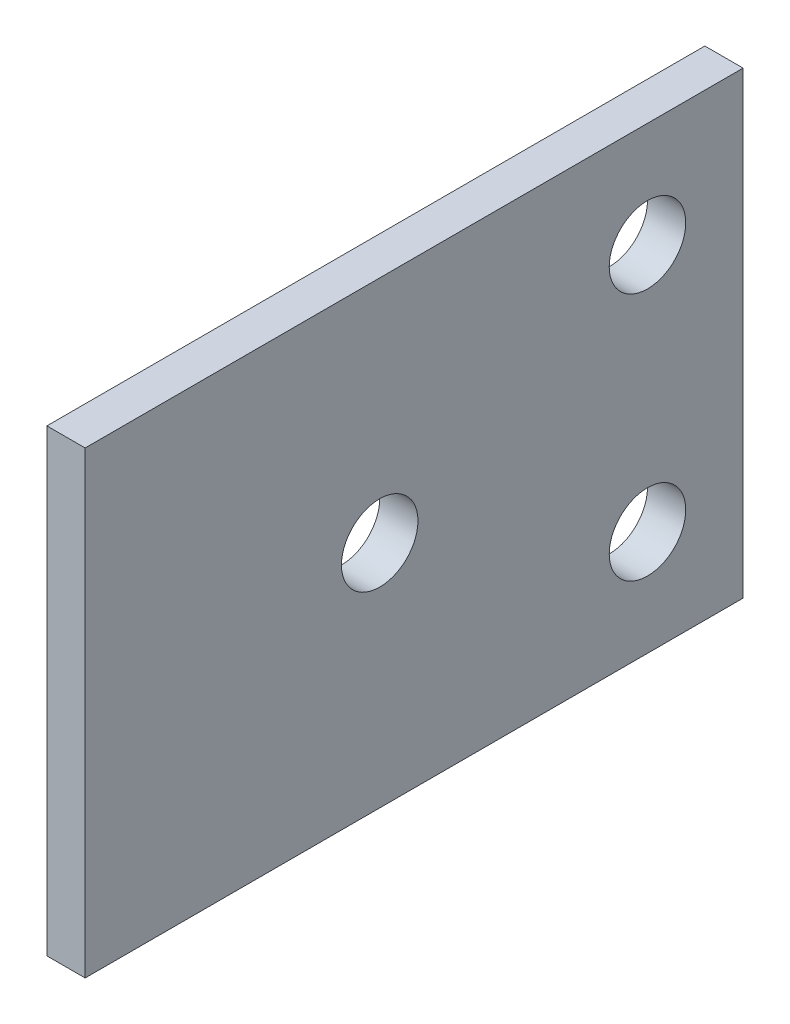
SolidWorks part; units mm, degrees
material "1023 Carbon Steel Sheet (SS)"
ref_plane "Front Plane" through (0, 0, 0) normal (0, 0, 1) x (1, 0, 0)
ref_plane "Top Plane" through (0, 0, 0) normal (0, 1, 0) x (1, 0, 0)
ref_plane "Right Plane" through (0, 0, 0) normal (1, 0, 0) x (0, 0, -1)
sketch "Sketch1" plane through (0, 0, 0) normal (1, 0, 0) x (0, 0, -1)
  line L1 (-86, -60) -> (86, -60)
  line L2 (-86, -60) -> (-86, 60)
  line L3 (-86, 60) -> (86, 60)
  line L4 (86, -60) -> (86, 60)
  line L5 (-86, -60) -> (86, 60) construction
  line L6 (-86, 60) -> (86, -60) construction
  point P0 (0, 0)
  dimension "D1" = 120
  dimension "D2" = 172
extrude "Boss-Extrude1" add sketch "Sketch1" along normal blind 10
sketch "Sketch2" plane through (10, 0, 0) normal (1, 0, 0) x (0, 0, -1)
  line L0 (-86, -60) -> (86, -60) construction
  line L1 (86, 60) -> (-86, 60) construction
  line L2 (86, -60) -> (86, 60) construction
  circle A0 centre (-9, 0) radius 10
  circle A1 centre (61, 32.5) radius 10
  circle A2 centre (61, -32.5) radius 10
  dimension "D1" = 20
  dimension "D2" = 20
  dimension "D3" = 20
  dimension "D4" = 65
  dimension "D5" = 27.5
  dimension "D6" = 27.5
  dimension "D7" = 25
  dimension "D8" = 70
extrude "Cut-Extrude1" cut sketch "Sketch2" against normal through all both and the other way through all
